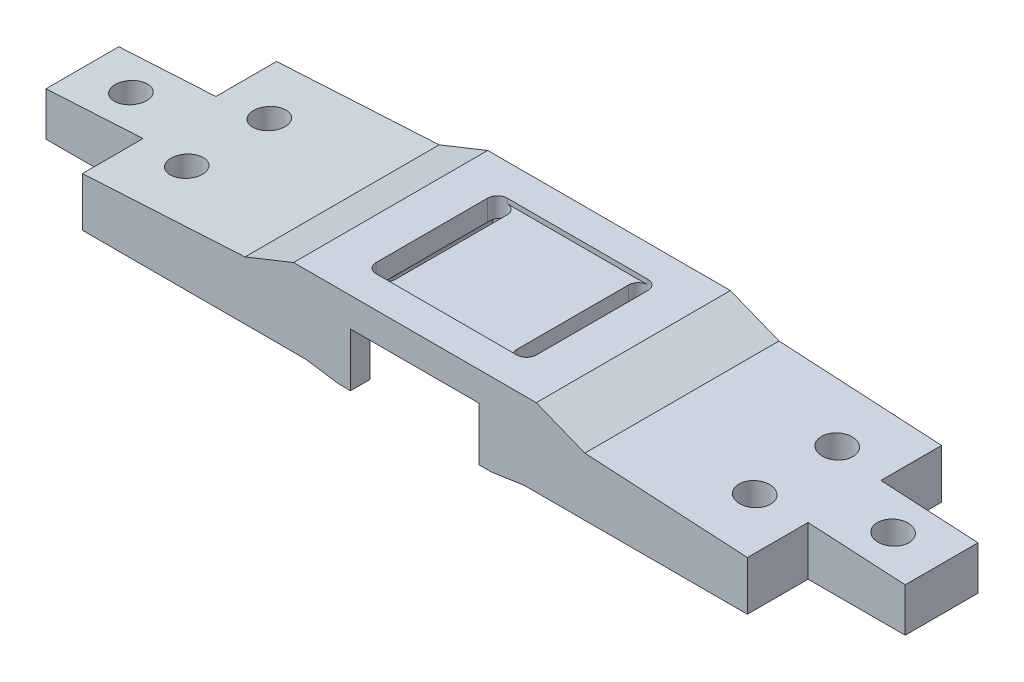
SolidWorks part; units mm, degrees
ref_plane "Front Plane" through (0, 0, 0) normal (0, 0, 1) x (1, 0, 0)
ref_plane "Top Plane" through (0, 0, 0) normal (0, 1, 0) x (1, 0, 0)
ref_plane "Right Plane" through (0, 0, 0) normal (1, 0, 0) x (0, 0, -1)
sketch "Sketch1" plane through (0, 0, 0) normal (0, 1, 0) x (1, 0, 0)
  line L0 (68.5, 20) -> (68.5, 7.5)
  line L1 (-68.5, 20) -> (68.5, 20)
  line L3 (-68.5, -20) -> (68.5, -20)
  line L5 (-68.5, 20) -> (68.5, -20) construction
  line L6 (-68.5, -20) -> (68.5, 20) construction
  line L7 (68.5, 7.5) -> (88.5, 7.5)
  line L8 (88.5, 7.5) -> (88.5, -7.5)
  line L9 (88.5, -7.5) -> (68.5, -7.5)
  line L10 (68.5, -7.5) -> (68.5, -20)
  line L11 (0, 0) -> (0, -116.996) construction
  line L12 (-68.5, -7.5) -> (-68.5, -20)
  line L13 (-88.5, -7.5) -> (-68.5, -7.5)
  line L14 (-88.5, 7.5) -> (-88.5, -7.5)
  line L15 (-68.5, 7.5) -> (-88.5, 7.5)
  line L16 (-68.5, 20) -> (-68.5, 7.5)
  circle A0 centre (-78.5, 0) radius 1.8
  circle A1 centre (-58.5, 8.5) radius 1.8
  circle A2 centre (-58.5, -8.5) radius 1.8
  circle A3 centre (58.5, -8.5) radius 1.8
  circle A4 centre (78.5, 0) radius 1.8
  circle A5 centre (58.5, 8.5) radius 1.8
  point P0 (0, 0)
  dimension "D6" = 3.6
  dimension "D1" = 137
  dimension "D2" = 40
  dimension "D3" = 20
  dimension "D4" = 15
  dimension "D5" = 12.5
  dimension "D7" = 7.5
  dimension "D8" = 10
  dimension "D9" = 10
  dimension "D10" = 1
  dimension "D11" = 10
  dimension "D12" = 1
extrude "Boss-Extrude1" add sketch "Sketch1" along normal blind 6
sketch "Sketch2" plane through (0, 0, -20) normal (0, 0, -1) x (-1, 0, 0)
  line L1 (-68.5, 6) -> (68.5, 6) construction
  line L4 (-88.5, 6) -> (-68.5, 6) construction
  line L5 (-88.5, 6) -> (88.5, 6)
  line L7 (-35, 12) -> (-88.5, 9)
  line L8 (-88.5, 9) -> (-88.5, 6)
  line L9 (-88.5, 6) -> (-88.5, 0) construction
  line L10 (35, 12) -> (88.5, 9)
  line L11 (88.5, 9) -> (88.5, 6)
  line L12 (88.5, 6) -> (88.5, 0) construction
  line L13 (35, 12) -> (25, 16)
  line L14 (25, 16) -> (-25, 16)
  line L15 (-25, 16) -> (-35, 12)
  dimension "D5" = 3
  dimension "D1" = 3
  dimension "D3" = 53.5
  dimension "D4" = 53.5
  dimension "D2" = 6
  dimension "D6" = 6
  dimension "D7" = 4
  dimension "D8" = 10
  dimension "D9" = 10
extrude "Boss-Extrude2" add sketch "Sketch2" against normal up to surface (40 mm away) up to face at (0, 3, 20)
sketch "Sketch3" plane through (0, 6, 0) normal (0, -1, 0) x (1, 0, 0)
  line L16 (88.5, 20) -> (88.5, 7.5) construction
  line L21 (-88.5, 20) -> (-68.5, 20)
  line L22 (-88.5, 20) -> (-88.5, 7.5)
  line L23 (-88.5, 7.5) -> (-68.5, 7.5)
  line L24 (-68.5, 20) -> (-68.5, 7.5)
  line L25 (-68.5, -7.5) -> (-88.5, -7.5)
  line L26 (-68.5, -7.5) -> (-68.5, -20)
  line L27 (-68.5, -20) -> (-88.5, -20)
  line L28 (-88.5, -7.5) -> (-88.5, -20)
  line L29 (68.5, 7.5) -> (88.5, 7.5)
  line L30 (68.5, 7.5) -> (68.5, 20)
  line L31 (68.5, 20) -> (88.5, 20)
  line L32 (88.5, 7.5) -> (88.5, 20)
  line L33 (68.5, -7.5) -> (88.5, -7.5)
  line L34 (68.5, -7.5) -> (68.5, -20)
  line L35 (68.5, -20) -> (88.5, -20)
  line L36 (88.5, -7.5) -> (88.5, -20)
extrude "Cut-Extrude1" cut sketch "Sketch3" against normal up to next
sketch "Sketch4" plane through (0, 16, 0) normal (0, 1, 0) x (1, 0, 0)
  circle A0 centre (-58.5, 8.5) radius 3.25
  circle A1 centre (-78.5, 0) radius 3.25
  circle A2 centre (-58.5, -8.5) radius 3.25
  circle A3 centre (58.5, 8.5) radius 3.25
  circle A4 centre (58.5, -8.5) radius 3.25
  circle A5 centre (78.5, 0) radius 3.25
  dimension "D1" = 6.5
extrude "Cut-Extrude2" cut sketch "Sketch4" against normal blind 12
sketch "Sketch5" plane through (0, 0, -20) normal (0, 0, -1) x (-1, 0, 0)
  line L0 (-22.5, 0) -> (-16, 10)
  line L1 (-68.5, 0) -> (68.5, 0) construction
  line L2 (-16, 10) -> (16, 10)
  line L3 (16, 10) -> (22.5, 0)
  line L4 (22.5, 0) -> (-22.5, 0)
  line L5 (68.5, 10.1215) -> (68.5, 0) construction
  dimension "D1" = 45
  dimension "D3" = 10
  dimension "D4" = 32
  dimension "D5" = 6.5
  dimension "D2" = 46
extrude "Cut-Extrude3" cut sketch "Sketch5" against normal up to next
sketch "Sketch6" plane through (0, 10, 0) normal (0, -1, 0) x (1, 0, 0)
  line L1 (-17.5, 13.5) -> (17.5, 13.5)
  line L2 (-17.5, 13.5) -> (-17.5, -13.5)
  line L3 (-17.5, -13.5) -> (17.5, -13.5)
  line L4 (17.5, 13.5) -> (17.5, -13.5)
  dimension "D1" = 27
  dimension "D2" = 13.5
  dimension "D3" = 35
  dimension "D4" = 17.5
extrude "Cut-Extrude4" cut sketch "Sketch6" against normal blind 2 and the other way up to next
fillet "Fillet1" radius 2 2 edges at (17.5, 12, 0) (-17.5, 12, 0)
sketch "Sketch7" plane through (0, 0, -20) normal (0, 0, -1) x (-1, 0, 0)
  line L0 (-22.5, 0) -> (-15.75, -1)
  line L1 (-16, 10) -> (-22.5, 0) construction
  line L2 (-15.75, -1) -> (-13.25, -1)
  line L3 (-13.25, -1) -> (-13.25, 10)
  line L4 (16, 10) -> (-16, 10) construction
  line L5 (-13.25, 10) -> (-16, 10)
  line L6 (-16, 10) -> (-22.5, 0)
  line L7 (0, 0) -> (0, -17.4167) construction
  line L8 (16, 10) -> (22.5, 0)
  line L9 (13.25, 10) -> (16, 10)
  line L10 (13.25, -1) -> (13.25, 10)
  line L11 (15.75, -1) -> (13.25, -1)
  line L12 (22.5, 0) -> (15.75, -1)
  dimension "D1" = 26.5
  dimension "D2" = 11
  dimension "D3" = 2.5
extrude "Boss-Extrude3" add sketch "Sketch7" against normal blind 4
mirror "Mirror1" about plane through (0, 0, 0) normal (0, 0, 1) of "Boss-Extrude3"
sketch "Sketch8" plane through (0, 12, 0) normal (0, -1, 0) x (1, 0, 0)
  line L0 (-14.5, 11.5) -> (-14.5, -11.5) construction
  line L1 (-12.5, 11.5) -> (-12.5, -11.5)
  line L2 (-16.5, 11.5) -> (-16.5, -11.5)
  line L3 (14.5, 11.5) -> (14.5, -11.5) construction
  line L4 (16.5, 11.5) -> (16.5, -11.5)
  line L5 (12.5, 11.5) -> (12.5, -11.5)
  arc A0 (-12.5, 11.5) -> (-16.5, 11.5) centre (-14.5, 11.5) ccw
  arc A1 (-16.5, -11.5) -> (-12.5, -11.5) centre (-14.5, -11.5) ccw
  arc A2 (16.5, 11.5) -> (12.5, 11.5) centre (14.5, 11.5) ccw
  arc A3 (12.5, -11.5) -> (16.5, -11.5) centre (14.5, -11.5) ccw
  point P2 (-14.5, 0)
  point P7 (14.5, 0)
  dimension "D1" = 2
  dimension "D2" = 2
  dimension "D3" = 29
  dimension "D4" = 14.5
  dimension "D5" = 23
  dimension "D6" = 23
extrude "Cut-Extrude5" cut sketch "Sketch8" against normal up to next and the other way up to next
sketch "Sketch10" plane through (0, 16, 0) normal (0, 1, 0) x (1, 0, 0)
  line L1 (-14.5, 13.5) -> (14.5, 13.5)
  line L2 (-14.5, 13.5) -> (-14.5, -13.5)
  line L3 (-14.5, -13.5) -> (14.5, -13.5)
  line L4 (14.5, 13.5) -> (14.5, -13.5)
  arc A2 (12.5, -11.5) -> (16.5, -11.5) centre (14.5, -11.5) ccw construction
  arc A3 (-12.5, 11.5) -> (-16.5, 11.5) centre (-14.5, 11.5) ccw construction
extrude "Cut-Extrude7" cut sketch "Sketch10" against normal blind 1
equation "\"D5@Sketch1\"=(\"D2@Sketch1\"-\"D4@Sketch1\")/2"
equation "\"D5@Sketch5\"=(\"D1@Sketch5\"-\"D4@Sketch5\")/2"
equation "\"D2@Sketch6\"=\"D1@Sketch6\"/2"
equation "\"D4@Sketch8\"=\"D3@Sketch8\"/2"
equation "\"D4@Sketch2\"=\"D3@Sketch2\""
